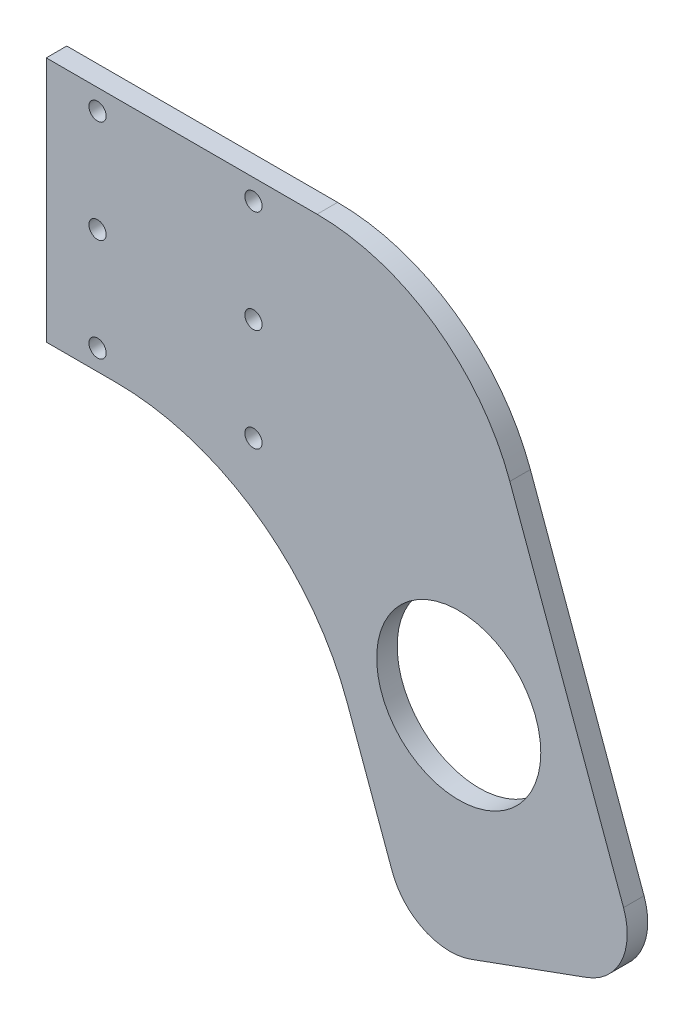
SolidWorks part; units mm, degrees
ref_plane "Front Plane" through (0, 0, 0) normal (0, 0, 1) x (1, 0, 0)
ref_plane "Top Plane" through (0, 0, 0) normal (0, 1, 0) x (1, 0, 0)
ref_plane "Right Plane" through (0, 0, 0) normal (1, 0, 0) x (0, 0, -1)
sketch "Sketch1" plane through (0, 0, 0) normal (0, 0, 1) x (1, 0, 0)
  line L0 (0, 0) -> (0, 50000) construction
  line L1 (0, 0) -> (50000, 0) construction
  line L2 (0, 56.5646) -> (-80, 56.5646) construction
  line L3 (0, 56.5646) -> (20.5212, 0.1831) construction
  line L4 (20.5212, 0.1831) -> (42.5081, -60.2255) construction
  line L5 (-80, 26.5646) -> (-80, 86.5646)
  line L6 (-80, 86.5646) -> (0, 86.5646)
  line L7 (-80, 26.5646) -> (-21.0062, 26.5646)
  line L8 (21.0062, 86.5646) -> (65.813, -36.541)
  line L9 (0, 86.5646) -> (21.0062, 86.5646)
  line L10 (-21.0062, 26.5646) -> (-21.0062, 86.5646) construction
  line L11 (-21.0062, 26.5646) -> (9.4314, -57.0622)
  line L12 (9.4314, -57.0622) -> (65.813, -36.541)
  line L13 (-67.5, 86.5646) -> (-67.5, 26.5646) construction
  line L14 (-29.5, 86.5646) -> (-29.5, 26.5646) construction
  circle A0 centre (20.5212, 0.1831) radius 20
  circle A1 centre (-67.5, 81.5646) radius 2.1
  circle A2 centre (-67.5, 56.5646) radius 2.1
  circle A3 centre (-67.5, 31.5646) radius 2.1
  circle A4 centre (-29.5, 81.5646) radius 2.1
  circle A5 centre (-29.5, 56.5646) radius 2.1
  circle A6 centre (-29.5, 31.5646) radius 2.1
  dimension "D7" = 40
  dimension "D10" = 4.2
  dimension "D1" = 110
  dimension "D2" = 60
  dimension "D3" = 80
  dimension "D4" = 30
  dimension "D5" = 30
  dimension "D6" = 50
  dimension "D8" = 58.9938
  dimension "D9" = 12.5
  dimension "D11" = 5
  dimension "D12" = 5
  dimension "D13" = 38
extrude "Boss-Extrude1" add sketch "Sketch1" along normal blind 5
fillet "Fillet1" radius 50 1 edges at (21.0062, 86.5646, 2.5)
fillet "Fillet2" radius 60 1 edges at (-21.0062, 26.5646, 2.5)
fillet "Fillet3" radius 15 2 edges at (65.813, -36.541, 2.5) (9.4314, -57.0622, 2.5)
